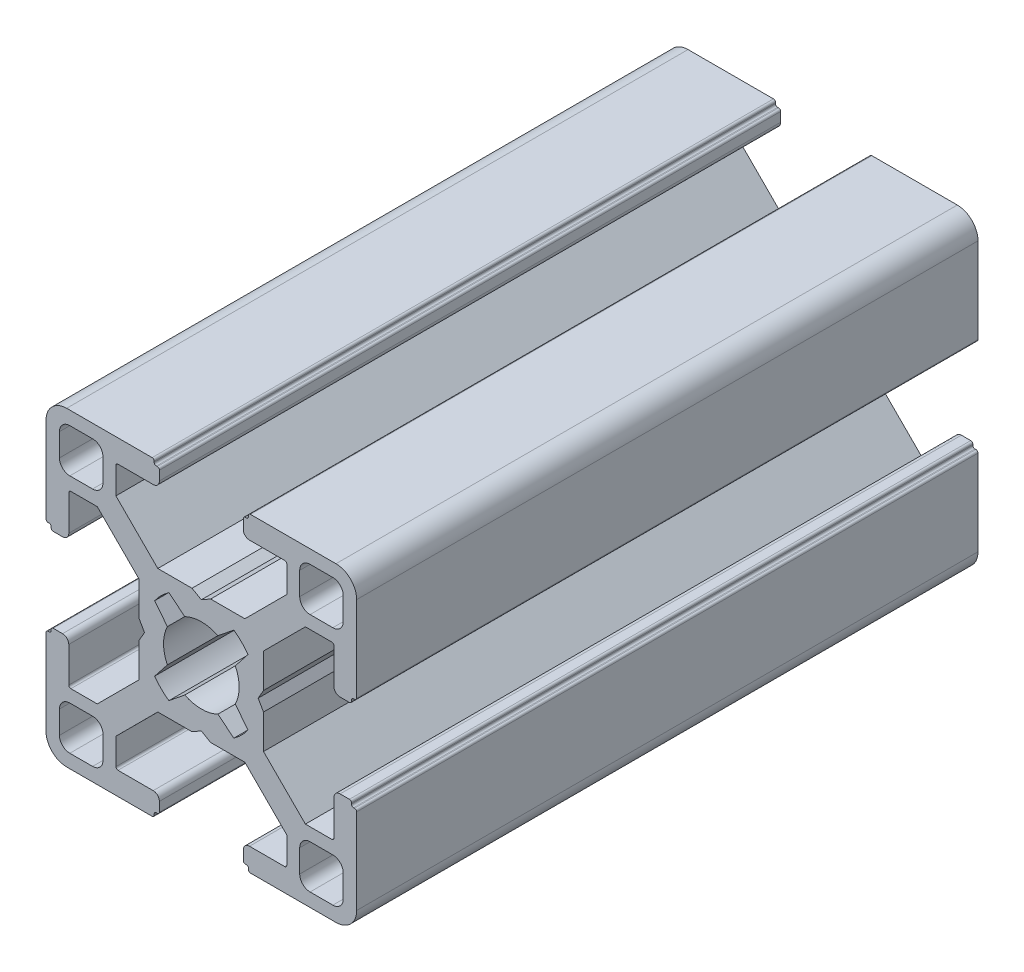
SolidWorks part; units mm, degrees
material "6061 Alloy"
ref_plane "Front" through (0, 0, 0) normal (0, 0, 1) x (1, 0, 0)
ref_plane "Top" through (0, 0, 0) normal (0, 1, 0) x (1, 0, 0)
ref_plane "Right" through (0, 0, 0) normal (1, 0, 0) x (0, 0, -1)
sketch "Sketch1" plane through (0, 0, 0) normal (0, 0, 1) x (1, 0, 0)
  line L0 (13.7, 12.7) -> (13.7, 10.5)
  line L1 (10.5, 9.5) -> (12.7, 9.5)
  line L2 (9.5, 12.7) -> (9.5, 10.5)
  line L3 (10.5, 13.7) -> (12.7, 13.7)
  line L4 (3.1359, 4.5184) -> (1.6001, 3.2806)
  line L5 (3.2806, 1.6001) -> (4.5053, 3.1547)
  line L6 (6.0045, 0.9) -> (5.4849, 0)
  line L7 (6.0045, 4.2045) -> (6.0045, 0.9)
  line L8 (0, -5.4849) -> (0.9, -6)
  line L9 (0.9, -6) -> (4.2045, -6)
  line L10 (4.2045, -6) -> (8.25, -10.05)
  line L11 (8.25, -10.05) -> (8.25, -12.6)
  line L12 (4.65, -12.8) -> (8.05, -12.8)
  line L13 (4.05, -14.3) -> (4.05, -13.4)
  line L14 (4.25, -14.5) -> (4.35, -14.5)
  line L15 (4.55, -14.8) -> (4.55, -14.7)
  line L16 (4.75, -15) -> (13, -15)
  line L17 (15, -13) -> (15, -4.75)
  line L18 (14.7, -4.55) -> (14.8, -4.55)
  line L19 (14.5, -4.35) -> (14.5, -4.25)
  line L20 (13.4, -4.05) -> (14.3, -4.05)
  line L21 (12.8, -8.05) -> (12.8, -4.65)
  line L22 (12.6, -8.25) -> (10.05, -8.25)
  line L23 (10.05, -8.25) -> (6.0045, -4.2045)
  line L24 (6.0045, -4.2045) -> (6.0045, -0.9)
  line L25 (6.0045, -0.9) -> (5.4849, 0)
  line L26 (10.05, 8.25) -> (6.0045, 4.2045)
  line L27 (12.6, 8.25) -> (10.05, 8.25)
  line L28 (12.8, 8.05) -> (12.8, 4.65)
  line L29 (13.4, 4.05) -> (14.3, 4.05)
  line L30 (14.5, 4.35) -> (14.5, 4.25)
  line L31 (14.7, 4.55) -> (14.8, 4.55)
  line L32 (15, 13) -> (15, 4.75)
  line L33 (4.75, 15) -> (13, 15)
  line L34 (4.55, 14.8) -> (4.55, 14.7)
  line L35 (4.25, 14.5) -> (4.35, 14.5)
  line L36 (4.05, 14.3) -> (4.05, 13.4)
  line L37 (4.65, 12.8) -> (8.05, 12.8)
  line L38 (8.25, 10.05) -> (8.25, 12.6)
  line L39 (4.2045, 6) -> (8.25, 10.05)
  line L40 (0.9, 6) -> (4.2045, 6)
  line L41 (0, 5.4849) -> (0.9, 6)
  line L42 (-13.7, -12.7) -> (-13.7, -10.5)
  line L43 (-10.5, -9.5) -> (-12.7, -9.5)
  line L44 (-9.5, -12.7) -> (-9.5, -10.5)
  line L45 (-10.5, -13.7) -> (-12.7, -13.7)
  line L46 (-3.1359, -4.5184) -> (-1.6001, -3.2806)
  line L47 (-3.2806, -1.6001) -> (-4.5053, -3.1547)
  line L48 (0, 5.4849) -> (-0.9, 6)
  line L49 (-0.9, 6) -> (-4.2045, 6)
  line L50 (-4.2045, 6) -> (-8.25, 10.05)
  line L51 (-8.25, 10.05) -> (-8.25, 12.6)
  line L52 (-4.65, 12.8) -> (-8.05, 12.8)
  line L53 (-4.05, 14.3) -> (-4.05, 13.4)
  line L54 (-4.25, 14.5) -> (-4.35, 14.5)
  line L55 (-4.55, 14.8) -> (-4.55, 14.7)
  line L56 (-4.75, 15) -> (-13, 15)
  line L57 (-15, 13) -> (-15, 4.75)
  line L58 (-14.7, 4.55) -> (-14.8, 4.55)
  line L59 (-14.5, 4.35) -> (-14.5, 4.25)
  line L60 (-13.4, 4.05) -> (-14.3, 4.05)
  line L61 (-12.8, 8.05) -> (-12.8, 4.65)
  line L62 (-12.6, 8.25) -> (-10.05, 8.25)
  line L63 (-10.05, 8.25) -> (-6.0045, 4.2045)
  line L64 (-6.0045, -0.9) -> (-5.4849, 0)
  line L65 (-6.0045, -4.2045) -> (-6.0045, -0.9)
  line L66 (-10.05, -8.25) -> (-6.0045, -4.2045)
  line L67 (-12.6, -8.25) -> (-10.05, -8.25)
  line L68 (-12.8, -8.05) -> (-12.8, -4.65)
  line L69 (-13.4, -4.05) -> (-14.3, -4.05)
  line L70 (-14.5, -4.35) -> (-14.5, -4.25)
  line L71 (-14.7, -4.55) -> (-14.8, -4.55)
  line L72 (-15, -13) -> (-15, -4.75)
  line L73 (-4.75, -15) -> (-13, -15)
  line L74 (-4.55, -14.8) -> (-4.55, -14.7)
  line L75 (-4.25, -14.5) -> (-4.35, -14.5)
  line L76 (-4.05, -14.3) -> (-4.05, -13.4)
  line L77 (3.2806, -1.6001) -> (4.5053, -3.1547)
  line L78 (3.1359, -4.5184) -> (1.6001, -3.2806)
  line L79 (-4.65, -12.8) -> (-8.05, -12.8)
  line L80 (-8.25, -10.05) -> (-8.25, -12.6)
  line L81 (-4.2045, -6) -> (-8.25, -10.05)
  line L82 (-0.9, -6) -> (-4.2045, -6)
  line L83 (0, -5.4849) -> (-0.9, -6)
  line L84 (10.5, -13.7) -> (12.7, -13.7)
  line L85 (9.5, -12.7) -> (9.5, -10.5)
  line L86 (10.5, -9.5) -> (12.7, -9.5)
  line L87 (13.7, -12.7) -> (13.7, -10.5)
  line L88 (-6.0045, 4.2045) -> (-6.0045, 0.9)
  line L89 (-6.0045, 0.9) -> (-5.4849, 0)
  line L90 (-3.2806, 1.6001) -> (-4.5053, 3.1547)
  line L91 (-3.1359, 4.5184) -> (-1.6001, 3.2806)
  line L92 (-10.5, 13.7) -> (-12.7, 13.7)
  line L93 (-9.5, 12.7) -> (-9.5, 10.5)
  line L94 (-10.5, 9.5) -> (-12.7, 9.5)
  line L95 (-13.7, 12.7) -> (-13.7, 10.5)
  line L96 (-23.4857, 0) -> (20.9308, 0) construction
  line L97 (0, 17.9563) -> (0, -17.361) construction
  arc A0 (13.7, 12.7) -> (12.7, 13.7) centre (12.7, 12.7) ccw
  arc A1 (12.7, 9.5) -> (13.7, 10.5) centre (12.7, 10.5) ccw
  arc A2 (9.5, 10.5) -> (10.5, 9.5) centre (10.5, 10.5) ccw
  arc A3 (10.5, 13.7) -> (9.5, 12.7) centre (10.5, 12.7) ccw
  arc A4 (1.6001, 3.2806) -> (-1.6001, 3.2806) centre (0, 0) ccw
  arc A5 (8.25, -12.6) -> (8.05, -12.8) centre (8.05, -12.6) cw
  arc A6 (4.65, -12.8) -> (4.05, -13.4) centre (4.65, -13.4) ccw
  arc A7 (4.05, -14.3) -> (4.25, -14.5) centre (4.25, -14.3) ccw
  arc A8 (4.35, -14.5) -> (4.55, -14.7) centre (4.35, -14.7) cw
  arc A9 (4.55, -14.8) -> (4.75, -15) centre (4.75, -14.8) ccw
  arc A10 (13, -15) -> (15, -13) centre (13, -13) ccw
  arc A11 (15, -4.75) -> (14.8, -4.55) centre (14.8, -4.75) ccw
  arc A12 (14.7, -4.55) -> (14.5, -4.35) centre (14.7, -4.35) cw
  arc A13 (14.5, -4.25) -> (14.3, -4.05) centre (14.3, -4.25) ccw
  arc A14 (13.4, -4.05) -> (12.8, -4.65) centre (13.4, -4.65) ccw
  arc A15 (12.8, -8.05) -> (12.6, -8.25) centre (12.6, -8.05) cw
  arc A16 (4.5053, 3.1547) -> (3.1359, 4.5184) centre (0, 0) ccw
  arc A17 (12.8, 8.05) -> (12.6, 8.25) centre (12.6, 8.05) ccw
  arc A18 (13.4, 4.05) -> (12.8, 4.65) centre (13.4, 4.65) cw
  arc A19 (14.5, 4.25) -> (14.3, 4.05) centre (14.3, 4.25) cw
  arc A20 (14.7, 4.55) -> (14.5, 4.35) centre (14.7, 4.35) ccw
  arc A21 (15, 4.75) -> (14.8, 4.55) centre (14.8, 4.75) cw
  arc A22 (13, 15) -> (15, 13) centre (13, 13) cw
  arc A23 (4.55, 14.8) -> (4.75, 15) centre (4.75, 14.8) cw
  arc A24 (4.35, 14.5) -> (4.55, 14.7) centre (4.35, 14.7) ccw
  arc A25 (4.05, 14.3) -> (4.25, 14.5) centre (4.25, 14.3) cw
  arc A26 (4.65, 12.8) -> (4.05, 13.4) centre (4.65, 13.4) cw
  arc A27 (8.25, 12.6) -> (8.05, 12.8) centre (8.05, 12.6) ccw
  arc A28 (-13.7, -12.7) -> (-12.7, -13.7) centre (-12.7, -12.7) ccw
  arc A29 (-12.7, -9.5) -> (-13.7, -10.5) centre (-12.7, -10.5) ccw
  arc A30 (-9.5, -10.5) -> (-10.5, -9.5) centre (-10.5, -10.5) ccw
  arc A31 (-10.5, -13.7) -> (-9.5, -12.7) centre (-10.5, -12.7) ccw
  arc A32 (-4.5053, -3.1547) -> (-3.1359, -4.5184) centre (0, 0) ccw
  arc A33 (-3.2806, 1.6001) -> (-3.2806, -1.6001) centre (0, 0) ccw
  arc A34 (-8.25, 12.6) -> (-8.05, 12.8) centre (-8.05, 12.6) cw
  arc A35 (-4.65, 12.8) -> (-4.05, 13.4) centre (-4.65, 13.4) ccw
  arc A36 (-4.05, 14.3) -> (-4.25, 14.5) centre (-4.25, 14.3) ccw
  arc A37 (-4.35, 14.5) -> (-4.55, 14.7) centre (-4.35, 14.7) cw
  arc A38 (-4.55, 14.8) -> (-4.75, 15) centre (-4.75, 14.8) ccw
  arc A39 (-13, 15) -> (-15, 13) centre (-13, 13) ccw
  arc A40 (-15, 4.75) -> (-14.8, 4.55) centre (-14.8, 4.75) ccw
  arc A41 (-14.7, 4.55) -> (-14.5, 4.35) centre (-14.7, 4.35) cw
  arc A42 (-14.5, 4.25) -> (-14.3, 4.05) centre (-14.3, 4.25) ccw
  arc A43 (-13.4, 4.05) -> (-12.8, 4.65) centre (-13.4, 4.65) ccw
  arc A44 (-12.8, 8.05) -> (-12.6, 8.25) centre (-12.6, 8.05) cw
  arc A45 (-4.5053, 3.1547) -> (-3.1359, 4.5184) centre (0, 0) cw
  arc A46 (-12.8, -8.05) -> (-12.6, -8.25) centre (-12.6, -8.05) ccw
  arc A47 (-13.4, -4.05) -> (-12.8, -4.65) centre (-13.4, -4.65) cw
  arc A48 (-14.5, -4.25) -> (-14.3, -4.05) centre (-14.3, -4.25) cw
  arc A49 (3.2806, 1.6001) -> (3.2806, -1.6001) centre (0, 0) cw
  arc A50 (4.5053, -3.1547) -> (3.1359, -4.5184) centre (0, 0) cw
  arc A51 (1.6001, -3.2806) -> (-1.6001, -3.2806) centre (0, 0) cw
  arc A52 (-14.7, -4.55) -> (-14.5, -4.35) centre (-14.7, -4.35) ccw
  arc A53 (-15, -4.75) -> (-14.8, -4.55) centre (-14.8, -4.75) cw
  arc A54 (-13, -15) -> (-15, -13) centre (-13, -13) cw
  arc A55 (-4.55, -14.8) -> (-4.75, -15) centre (-4.75, -14.8) cw
  arc A56 (10.5, -13.7) -> (9.5, -12.7) centre (10.5, -12.7) cw
  arc A57 (9.5, -10.5) -> (10.5, -9.5) centre (10.5, -10.5) cw
  arc A58 (12.7, -9.5) -> (13.7, -10.5) centre (12.7, -10.5) cw
  arc A59 (13.7, -12.7) -> (12.7, -13.7) centre (12.7, -12.7) cw
  arc A60 (-4.35, -14.5) -> (-4.55, -14.7) centre (-4.35, -14.7) ccw
  arc A61 (-4.05, -14.3) -> (-4.25, -14.5) centre (-4.25, -14.3) cw
  arc A62 (-4.65, -12.8) -> (-4.05, -13.4) centre (-4.65, -13.4) cw
  arc A63 (-8.25, -12.6) -> (-8.05, -12.8) centre (-8.05, -12.6) ccw
  arc A64 (-10.5, 13.7) -> (-9.5, 12.7) centre (-10.5, 12.7) cw
  arc A65 (-9.5, 10.5) -> (-10.5, 9.5) centre (-10.5, 10.5) cw
  arc A66 (-12.7, 9.5) -> (-13.7, 10.5) centre (-12.7, 10.5) cw
  arc A67 (-13.7, 12.7) -> (-12.7, 13.7) centre (-12.7, 12.7) cw
  point P81 (15, 15)
  point P82 (0, 15)
  point P203 (0, -15)
  point P204 (15, -15)
  point P206 (0, 0)
  point P207 (15, 0)
  point P219 (-15, 0)
  point P220 (-15, -15)
  point P221 (-15, 15)
extrude "Base-Extrude" add sketch "Sketch1" against normal blind 60
sketch "草图2" plane through (15, 0, 0) normal (1, 0, 0) x (0, 0, -1)
  line L0 (0, 15) -> (30, -15)
  line L1 (60, -15) -> (0, -15) construction
  line L2 (0, 4.75) -> (0, 13) construction
  line L3 (0, 15) -> (0, -15)
  line L4 (0, -15) -> (30, -15)
  line L5 (-13.0087, 11.9543) -> (-11.263, 12.8943)
  dimension "D1" = 45
